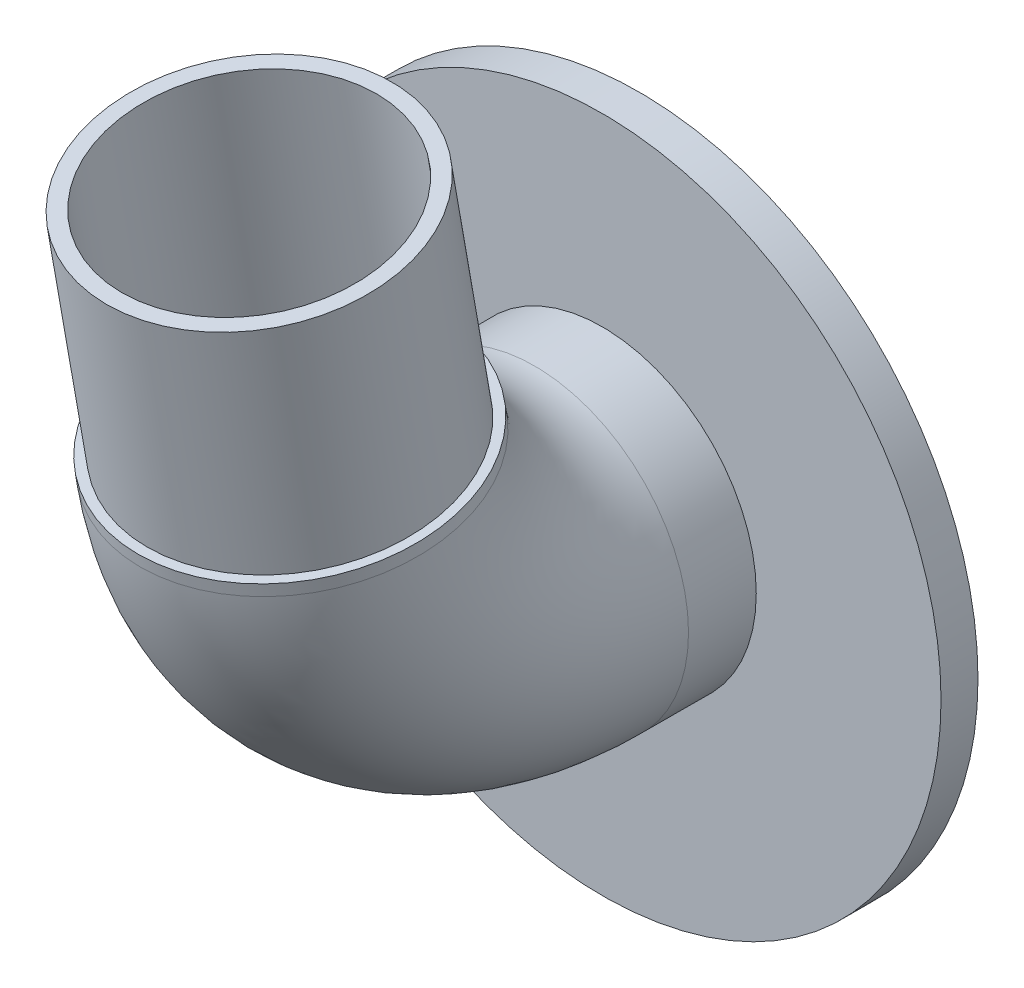
SolidWorks part; units mm, degrees
ref_plane "Plan de face" through (0, 0, 0) normal (0, 0, 1) x (1, 0, 0)
ref_plane "Plan de dessus" through (0, 0, 0) normal (0, 1, 0) x (1, 0, 0)
ref_plane "Plan de droite" through (0, 0, 0) normal (1, 0, 0) x (0, 0, -1)
sketch "Esquisse1" plane through (0, 0, 0) normal (0, 0, 1) x (1, 0, 0)
  circle A0 centre (0, 0) radius 55
  circle A1 centre (0, 0) radius 25
  dimension "D1" = 50
  dimension "D2" = 110
extrude "Boss.-Extru.1" add sketch "Esquisse1" along normal blind 6
sketch "Esquisse2" plane through (0, 0, 6) normal (0, 0, 1) x (1, 0, 0)
  circle A0 centre (0, 0) radius 21
  circle A1 centre (0, 0) radius 25
  circle A2 centre (0, 0) radius 25 construction
  dimension "D1" = 4
extrude "Boss.-Extru.2" add sketch "Esquisse2" along normal blind 1 and the other way up to surface (6 mm away) other way up to face at (55, 0, 0)
sketch "Esquisse3" plane through (0, 0, 0) normal (1, 0, 0) x (0, 0, -1)
  line L0 (-7, 0) -> (-17, 0)
  line L1 (-7, 25) -> (-7, -25) construction
  line L2 (-56.3923, 33.0541) -> (-63.3382, 72.4464)
  arc A0 (-17, 0) -> (-56.3923, 33.0541) centre (-17, 40) cw
  point P8 (-39.3666, 0)
  point P9 (-96.2585, 12.9011)
  dimension "D4" = 40
  dimension "D3" = 100
  dimension "D1" = 40
  dimension "D2" = 10
sketch "Esquisse4" plane through (0, 0, 7) normal (0, 0, 1) x (1, 0, 0)
  circle A0 centre (0, 0) radius 21 construction
  circle A1 centre (0, 0) radius 25 construction
  circle A3 centre (0, 0) radius 25
  circle A4 centre (0, 0) radius 21
sweep "Balayage5" add profiles "Esquisse4" path "Esquisse3"
sketch "Esquisse8" plane through (0, 81.0933, 14.2989) normal (0, 0.9848, 0.1736) x (1, 0, 0)
  circle A1 centre (0, -49.7958) radius 23.5
  circle A3 centre (0, -49.7958) radius 25
  circle A4 centre (0, -49.7958) radius 25 construction
  dimension "D1" = 47
extrude "Enlèv. mat.-Extru.1" cut sketch "Esquisse8" against normal blind 38
